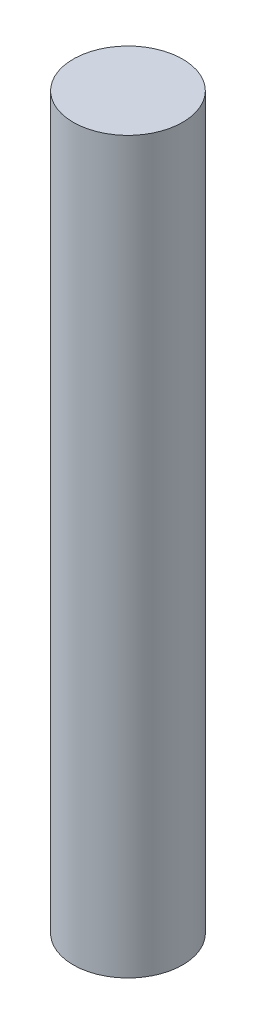
SolidWorks part; units mm, degrees
ref_plane "Front Plane" through (0, 0, 0) normal (0, 0, 1) x (1, 0, 0)
ref_plane "Top Plane" through (0, 0, 0) normal (0, 1, 0) x (1, 0, 0)
ref_plane "Right Plane" through (0, 0, 0) normal (1, 0, 0) x (0, 0, -1)
sketch "Sketch1" plane through (0, 0, 0) normal (0, 1, 0) x (1, 0, 0)
  circle A0 centre (0, 1.4399) radius 1.5
  dimension "D1" = 3
extrude "Boss-Extrude1" add sketch "Sketch1" along normal blind 20
